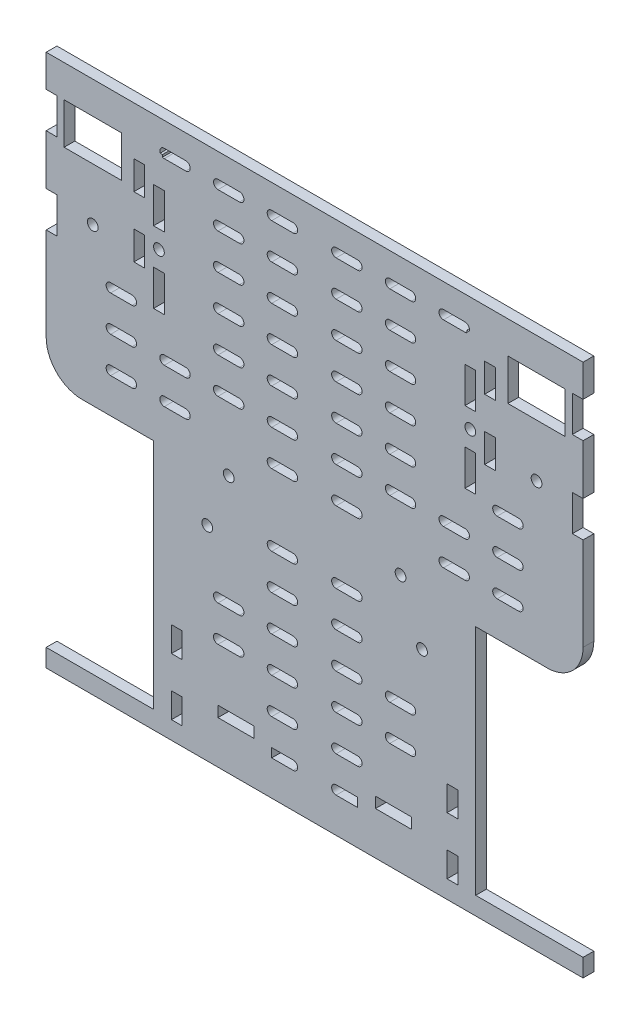
SolidWorks part; units mm, degrees
ref_plane "Alzado" through (0, 0, 0) normal (0, 0, 1) x (1, 0, 0)
ref_plane "Planta" through (0, 0, 0) normal (0, 1, 0) x (1, 0, 0)
ref_plane "Vista lateral" through (0, 0, 0) normal (1, 0, 0) x (0, 0, -1)
sketch "Croquis3" plane through (0, 0, 0) normal (0, 0, 1) x (1, 0, 0)
  line L1 (75, -75) -> (-75, -75)
  line L2 (75, -75) -> (75, 75)
  line L3 (75, 75) -> (-75, 75)
  line L4 (-75, -75) -> (-75, 75)
  line L5 (75, -75) -> (-75, 75) construction
  line L6 (75, 75) -> (-75, -75) construction
  line L11 (-75, -5) -> (-45, -5)
  line L13 (-75, -5) -> (-75, -70)
  line L18 (-75, -70) -> (-45, -70)
  line L19 (-45, -5) -> (-45, -70)
  line L24 (75, -70) -> (45, -70)
  line L25 (75, -70) -> (75, -5)
  line L26 (75, -5) -> (45, -5)
  line L27 (45, -70) -> (45, -5)
  point P0 (0, 0)
  dimension "D1" = 150
  dimension "D2" = 65
  dimension "D6" = 30
  dimension "D7" = 30
  dimension "D8" = 65
  dimension "D9" = 5
  dimension "D10" = 150
extrude "Saliente-Extruir1" add sketch "Croquis3" along normal blind 3
sketch "Croquis19" plane through (0, 0, 0) normal (0, 0, 1) x (1, 0, 0)
  line L0 (75, 75) -> (-75, 75) construction
  line L5 (-75, -5) -> (-75, 75) construction
  line B0 (-69, 31.75) -> (-55, 31.75) construction
  line B1 (-69, 62.75) -> (-69, 31.75) construction
  line B2 (-55, 62.75) -> (-69, 62.75) construction
  line B3 (-55, 31.75) -> (-55, 62.75) construction
  line B4 (-57, 56.5) -> (-57, 62) construction
  line B5 (-67, 56.5) -> (-57, 56.5) construction
  line B6 (-67, 62) -> (-67, 56.5) construction
  line B7 (-57, 62) -> (-67, 62) construction
  line B8 (-57, 34.35) -> (-67, 34.35) construction
  line B9 (-67, 34.35) -> (-67, 31.85) construction
  line B10 (-67, 31.85) -> (-57, 31.85) construction
  line B11 (-57, 31.85) -> (-57, 34.35) construction
  line B12 (-65.4, 33.45) -> (-66.1, 33.45) construction
  line B13 (-66.1, 33.45) -> (-66.1, 32.75) construction
  line B14 (-66.1, 32.75) -> (-65.4, 32.75) construction
  line B15 (-65.4, 32.75) -> (-65.4, 33.45) construction
  line B16 (-62.9, 33.45) -> (-63.6, 33.45) construction
  line B17 (-63.6, 33.45) -> (-63.6, 32.75) construction
  line B18 (-63.6, 32.75) -> (-62.9, 32.75) construction
  line B19 (-62.9, 32.75) -> (-62.9, 33.45) construction
  line B20 (-60.4, 33.45) -> (-61.1, 33.45) construction
  line B21 (-61.1, 33.45) -> (-61.1, 32.75) construction
  line B22 (-61.1, 32.75) -> (-60.4, 32.75) construction
  line B23 (-60.4, 32.75) -> (-60.4, 33.45) construction
  line B24 (-57.9, 33.45) -> (-58.6, 33.45) construction
  line B25 (-58.6, 33.45) -> (-58.6, 32.75) construction
  line B26 (-58.6, 32.75) -> (-57.9, 32.75) construction
  line B27 (-57.9, 32.75) -> (-57.9, 33.45) construction
  circle B28 centre (-62, 38.75) radius 1.5
  circle B29 centre (-60.25, 59.25) radius 1.5 construction
  circle B30 centre (-63.75, 59.25) radius 1.5 construction
  line B31 (-70, 53.5) -> (-54, 53.5)
  line B32 (-54, 53.5) -> (-54, 65)
  line B33 (-54, 65) -> (-70, 65)
  line B34 (-70, 65) -> (-70, 53.5)
  dimension "D1" = 10
  dimension "D2" = 5
sketch_block_instance "Bloque2-1"
sketch_block "Bloque2" parameters "D1"=3
extrude "Cortar-Extruir5" cut sketch "Croquis19" along normal blind 5
sketch "Croquis35" plane through (0, 0, 0) normal (0, 0, 1) x (1, 0, 0)
  line L0 (-45, -5) -> (-45, -70) construction
  line L1 (-40, -47) -> (-37, -47)
  line L2 (-40, -47) -> (-40, -54)
  line L3 (-40, -54) -> (-37, -54)
  line L4 (-37, -47) -> (-37, -54)
  line L5 (-40, -63) -> (-37, -63)
  line L6 (-40, -63) -> (-40, -70)
  line L7 (-40, -70) -> (-37, -70)
  line L8 (-37, -63) -> (-37, -70)
  line L9 (75, -75) -> (-75, -75) construction
  line L11 (-27, -63) -> (-17, -63)
  line L12 (-27, -63) -> (-27, -60)
  line L13 (-27, -60) -> (-17, -60)
  line L14 (-17, -63) -> (-17, -60)
  point P16 (-27, -61.5)
  dimension "D1" = 3
  dimension "D2" = 7
  dimension "D3" = 7
  dimension "D4" = 23
  dimension "D5" = 5
  dimension "D6" = 5
  dimension "D7" = 3
  dimension "D8" = 10
  dimension "D9" = 10
extrude "Cortar-Extruir7" cut sketch "Croquis35" along normal blind 3
sketch "Croquis36" plane through (0, 0, 0) normal (0, 0, 1) x (1, 0, 0)
  line L0 (-75, -5) -> (-75, 75) construction
  line L1 (-75, 65) -> (-72, 65)
  line L2 (-75, 65) -> (-75, 55)
  line L3 (-75, 55) -> (-72, 55)
  line L4 (-72, 65) -> (-72, 55)
  line L5 (75, 75) -> (-75, 75) construction
  line L6 (-75, 41) -> (-72, 41)
  line L7 (-75, 41) -> (-75, 31)
  line L8 (-75, 31) -> (-72, 31)
  line L9 (-72, 41) -> (-72, 31)
  dimension "D1" = 10
  dimension "D2" = 10
  dimension "D3" = 10
  dimension "D4" = 14
  dimension "D5" = 3
extrude "Cortar-Extruir8" cut sketch "Croquis36" along normal blind 3
sketch "Croquis37" plane through (0, 0, 0) normal (0, 0, 1) x (1, 0, 0)
  line L0 (-45, 47) -> (-42, 37) construction
  line L1 (45, 27) -> (-45, 27) construction
  line L2 (45, 27) -> (45, 57) construction
  line L3 (45, 57) -> (-45, 57) construction
  line L4 (-45, 27) -> (-45, 57) construction
  line L5 (45, 27) -> (-45, 57) construction
  line L6 (45, 57) -> (-45, 27) construction
  line L7 (-45, 57) -> (-42, 57)
  line L8 (-45, 57) -> (-45, 47)
  line L9 (-45, 47) -> (-42, 47)
  line L10 (-42, 57) -> (-42, 47)
  line L11 (-45, 27) -> (-42, 27)
  line L12 (-45, 27) -> (-45, 37)
  line L13 (-45, 37) -> (-42, 37)
  line L14 (-42, 27) -> (-42, 37)
  circle A0 centre (-43.5, 42) radius 1.5
  point P0 (0, 42)
  dimension "D4" = 3
  dimension "D1" = 90
  dimension "D2" = 30
  dimension "D3" = 3
  dimension "D5" = 10
  dimension "D6" = 10
  dimension "D7" = 42
extrude "Cortar-Extruir9" cut sketch "Croquis37" along normal blind 5
sketch "Croquis38" plane through (0, 0, 0) normal (0, 0, 1) x (1, 0, 0)
  line L0 (-70, 65) -> (-54, 65) construction
  line L1 (-50.5, 35.5) -> (-47.5, 35.5) construction
  line L2 (-50.5, 35.5) -> (-50.5, 60.5) construction
  line L3 (-50.5, 60.5) -> (-47.5, 60.5) construction
  line L4 (-47.5, 35.5) -> (-47.5, 60.5) construction
  line L5 (-50.5, 35.5) -> (-47.5, 60.5) construction
  line L6 (-50.5, 60.5) -> (-47.5, 35.5) construction
  line L7 (-50.5, 60.5) -> (-47.5, 60.5)
  line L8 (-50.5, 60.5) -> (-50.5, 52.5)
  line L9 (-50.5, 52.5) -> (-47.5, 52.5)
  line L10 (-47.5, 60.5) -> (-47.5, 52.5)
  line L11 (-47.5, 35.5) -> (-50.5, 35.5)
  line L12 (-47.5, 35.5) -> (-47.5, 43.5)
  line L13 (-47.5, 43.5) -> (-50.5, 43.5)
  line L14 (-50.5, 35.5) -> (-50.5, 43.5)
  line L15 (-45, 47) -> (-45, 57) construction
  point P0 (-49, 48)
  dimension "D1" = 3
  dimension "D2" = 25
  dimension "D3" = 8
  dimension "D4" = 8
  dimension "D5" = 4.5
  dimension "D6" = 2.5
extrude "Cortar-Extruir10" cut sketch "Croquis38" along normal blind 10
sketch "Croquis45" plane through (0, 0, 0) normal (0, 0, 1) x (1, 0, 0)
  line L1 (30, -18) -> (24, -18) construction
  line L2 (30, -18) -> (30, -3) construction
  line L3 (30, -3) -> (24, -3) construction
  line L4 (24, -18) -> (24, -3) construction
  line L5 (30, -18) -> (24, -3) construction
  line L6 (30, -3) -> (24, -18) construction
  line L7 (75, -75) -> (-75, -75) construction
  line L8 (75, -5) -> (75, 75) construction
  circle A0 centre (24, -3) radius 1.5
  circle A1 centre (30, -18) radius 1.5
  point P0 (27, -10.5)
  dimension "D1" = 3
  dimension "D2" = 51
  dimension "D3" = 72
  dimension "D4" = 3
  dimension "D5" = 15
  dimension "D6" = 6
extrude "Cortar-Extruir14" cut sketch "Croquis45" along normal through all
mirror "Simetría1" about plane through (0, 0, 0) normal (1, 0, 0) of "Cortar-Extruir14", "Cortar-Extruir9", "Cortar-Extruir8", "Cortar-Extruir7", "Cortar-Extruir5", "Cortar-Extruir10"
fillet "Redondeo1" radius 10 2 edges at (75, -5, 1.5) (-75, -5, 1.5)
sketch "Croquis40" plane through (0, 0, 0) normal (0, 0, 1) x (1, 0, 0)
  point P9 (54, 56)
  point P10 (24, 56)
  point P12 (39, 26)
  point P40 (24, 26)
  point P74 (24, 66)
  point P95 (9, 56)
  point P97 (39, 36)
  point P103 (54, 36)
  point P104 (9, 66)
  point P110 (54, 46)
  point P112 (39, 56)
  point P118 (24, 6)
  point P120 (39, 66)
  point P125 (39, 46)
  point P128 (9, 16)
  point P132 (24, 36)
  point P136 (9, 26)
  point P139 (69, 46)
  point P144 (9, 36)
  point P146 (69, 36)
  point P152 (9, 46)
  point P159 (24, 16)
  point P166 (69, 56)
  point P173 (69, 66)
  point P195 (24, 46)
  point P201 (54, 66)
  point P276 (39, 26)
  point P283 (39, 36)
  point P290 (54, 36)
  point P297 (54, 46)
  point P304 (24, 6)
  point P311 (39, 46)
  point P318 (24, 36)
  point P325 (69, 46)
  point P332 (69, 36)
  point P339 (69, 56)
  point P346 (69, 66)
  point P353 (24, 46)
  point P360 (54, 66)
  point P367 (54, 56)
  point P374 (39, 26)
  point P381 (39, 36)
  point P388 (54, 36)
  point P395 (54, 46)
  point P402 (24, 6)
  point P409 (39, 46)
  point P416 (24, 36)
  point P423 (69, 46)
  point P430 (69, 36)
  point P437 (69, 56)
  point P444 (69, 66)
  point P451 (24, 46)
  point P458 (54, 66)
  point P465 (54, 56)
  point P472 (39, 26)
  point P479 (39, 36)
  point P486 (54, 36)
  point P493 (54, 46)
  point P500 (24, 6)
  point P507 (39, 46)
  point P514 (24, 36)
  point P521 (69, 46)
  point P528 (69, 36)
  point P535 (69, 56)
  point P542 (69, 66)
  point P549 (24, 46)
  point P556 (54, 66)
  point P563 (54, 56)
  point P570 (39, 26)
  point P577 (39, 36)
  point P584 (54, 36)
  point P591 (54, 46)
  point P598 (24, 6)
  point P605 (39, 46)
  point P612 (24, 36)
  point P619 (69, 46)
  point P626 (69, 36)
  point P633 (69, 56)
  point P640 (69, 66)
  point P647 (24, 46)
  point P654 (54, 66)
  point P661 (54, 56)
  line B0 (-70, 48.5) -> (-55.5, 48.5)
  line B1 (-32, -68) -> (-32, -70)
  line B2 (-49, 65.5) -> (-49, 70)
  line B3 (-67, 34.5967) -> (-67, 26)
  line B4 (37, 35.5) -> (37, 22)
  line B5 (-37, 48.5) -> (-37, 62)
  line B6 (-50, 30.5) -> (-50, 22)
  line B7 (42.5, 62) -> (37, 62)
  line B8 (67, 42.9033) -> (67, 46)
  line B9 (32, -68) -> (32, -70)
  line B10 (-28, -9) -> (-15, -9)
  line B11 (-15, 4) -> (-15, 11)
  line B12 (-15, 11) -> (-28, 11)
  line B13 (-28, 11) -> (-28, -9)
  line B14 (-28, -35) -> (-15, -35)
  line B15 (-15, -35) -> (-15, -15)
  line B16 (-15, -15) -> (-28, -15)
  line B17 (-28, -15) -> (-28, -35)
  line B18 (-17, -9) -> (1, -9)
  line B19 (1, 4) -> (-15, 4)
  line B20 (-32, -68) -> (-12, -68)
  line B21 (-12, -68) -> (-12, -55)
  line B22 (-12, -55) -> (-32, -55)
  line B23 (-32, -42) -> (-32, -55)
  line B24 (-32, -42) -> (-40, -42)
  line B25 (-37, 35.5) -> (-12, 35.5)
  line B26 (-12, 35.5) -> (-12, 48.5)
  line B27 (-12, 48.5) -> (-37, 48.5)
  line B28 (-50, 22) -> (-37, 22)
  line B29 (-37, 22) -> (-37, 35.5)
  line B30 (-37, 62) -> (-42.5, 62)
  line B31 (-55.5, 30.5) -> (-50, 30.5)
  line B32 (-55.5, 48.5) -> (-55.5, 30.5)
  line B33 (-42.5, 65.5) -> (-49, 65.5)
  line B34 (-42.5, 62) -> (-42.5, 65.5)
  line B35 (49, 70) -> (49, 65.5)
  line B36 (55.5, 48.5) -> (70, 48.5)
  line B37 (28, -9) -> (28, 11)
  line B38 (28, 11) -> (15, 11)
  line B39 (15, 11) -> (15, 4)
  line B40 (15, -9) -> (28, -9)
  line B41 (28, -35) -> (28, -15)
  line B42 (28, -15) -> (15, -15)
  line B43 (15, -15) -> (15, -35)
  line B44 (15, -35) -> (28, -35)
  line B45 (15, 4) -> (-1, 4)
  line B46 (-1, -9) -> (17, -9)
  line B47 (32, -55) -> (12, -55)
  line B48 (12, -55) -> (12, -68)
  line B49 (12, -68) -> (32, -68)
  line B50 (32, -42) -> (32, -55)
  line B51 (40, -42) -> (32, -42)
  line B52 (37, 48.5) -> (12, 48.5)
  line B53 (12, 48.5) -> (12, 35.5)
  line B54 (12, 35.5) -> (37, 35.5)
  line B55 (50, 22) -> (50, 30.5)
  line B56 (37, 62) -> (37, 48.5)
  line B57 (37, 22) -> (50, 22)
  line B58 (55.5, 30.5) -> (55.5, 48.5)
  line B59 (50, 30.5) -> (55.5, 30.5)
  line B60 (42.5, 65.5) -> (42.5, 62)
  line B61 (49, 65.5) -> (42.5, 65.5)
  line B62 (49, 70) -> (-49, 70)
  line B63 (-70, 48.5) -> (-70, 46)
  line B64 (-70, 46) -> (-67, 46)
  line B65 (-67, 46) -> (-67, 42.9033)
  line B66 (-67, 26) -> (-70, 26)
  line B67 (-70, 26) -> (-70, 5)
  line B68 (-65, 0) -> (-40, 0)
  line B69 (-40, 0) -> (-40, -42)
  line B70 (-32, -70) -> (32, -70)
  line B71 (40, -42) -> (40, 0)
  line B72 (40, 0) -> (65, 0)
  line B73 (70, 5) -> (70, 26)
  line B74 (70, 26) -> (67, 26)
  line B75 (67, 26) -> (67, 34.5967)
  line B76 (67, 46) -> (70, 46)
  line B77 (70, 46) -> (70, 48.5)
  arc B78 (-67, 34.5967) -> (-67, 42.9033) centre (-62, 38.75) ccw
  arc B79 (67, 42.9033) -> (67, 34.5967) centre (62, 38.75) ccw
  arc B80 (-70, 5) -> (-65, 0) centre (-65, 5) ccw
  arc B81 (65, 0) -> (70, 5) centre (65, 5) ccw
sketch_block_instance "Bloque3-1"
sketch_block "Bloque3"
sketch "Croquis42" plane through (0, 0, 0) normal (0, 0, 1) x (1, 0, 0)
  line L4 (6, 6) -> (12, 6) construction
  line L5 (6, 7.25) -> (12, 7.25)
  line L6 (6, 4.75) -> (12, 4.75)
  line L14 (36, 6) -> (42, 6) construction
  line L15 (36, 7.25) -> (42, 7.25)
  line L20 (36, 4.75) -> (42, 4.75)
  line L21 (51, 6) -> (57, 6) construction
  line L22 (51, 7.25) -> (57, 7.25)
  line L23 (51, 4.75) -> (57, 4.75)
  line L31 (21, 16) -> (27, 16) construction
  line L36 (21, 17.25) -> (27, 17.25)
  line L37 (21, 14.75) -> (27, 14.75)
  line L38 (36, 16) -> (42, 16) construction
  line L39 (36, 17.25) -> (42, 17.25)
  line L44 (36, 14.75) -> (42, 14.75)
  line L45 (51, 16) -> (57, 16) construction
  line L47 (51, 17.25) -> (57, 17.25)
  line L53 (51, 14.75) -> (57, 14.75)
  line L63 (21, 26) -> (27, 26) construction
  line L70 (21, 27.25) -> (27, 27.25)
  line L71 (21, 24.75) -> (27, 24.75)
  line L85 (51, 26) -> (57, 26) construction
  line L86 (51, 27.25) -> (57, 27.25)
  line L87 (51, 24.75) -> (57, 24.75)
  line L109 (42.5, 65.5) -> (42.5, 62) construction
  line L116 (49, 65.5) -> (42.5, 65.5) construction
  line L148 (21, 56) -> (27, 56) construction
  line L149 (21, 57.25) -> (27, 57.25)
  line L150 (21, 54.75) -> (27, 54.75)
  line L158 (42.5, 65.5) -> (42.5, 64.8544)
  line L165 (43.1456, 65.5) -> (42.5, 65.5)
  line L172 (21, 66) -> (27, 66) construction
  line L173 (21, 67.25) -> (27, 67.25)
  line L174 (21, 64.75) -> (27, 64.75)
  line L175 (36, 66) -> (42, 66) construction
  line L180 (36, 67.25) -> (42, 67.25)
  line L181 (36, 64.75) -> (42, 64.75)
  line L220 (6, 16) -> (12, 16) construction
  line L221 (6, 17.25) -> (12, 17.25)
  line L222 (6, 14.75) -> (12, 14.75)
  line L223 (6, 26) -> (12, 26) construction
  line L224 (6, 27.25) -> (12, 27.25)
  line L225 (6, 24.75) -> (12, 24.75)
  line L232 (6, 56) -> (12, 56) construction
  line L233 (6, 57.25) -> (12, 57.25)
  line L234 (6, 54.75) -> (12, 54.75)
  line L235 (6, 66) -> (12, 66) construction
  line L236 (6, 67.25) -> (12, 67.25)
  line L237 (6, 64.75) -> (12, 64.75)
  line L1105 (36, 66) -> (42, 66) construction
  line L1106 (36, 67.25) -> (42, 67.25)
  line L1107 (36, 64.75) -> (42, 64.75)
  line L1108 (36, 56) -> (42, 56) construction
  line L1109 (36, 57.25) -> (42, 57.25)
  line L1110 (36, 54.75) -> (42, 54.75)
  line L1111 (6, 46) -> (12, 46) construction
  line L1112 (6, 47.25) -> (12, 47.25)
  line L1113 (6, 44.75) -> (12, 44.75)
  line L1114 (6, 36) -> (12, 36) construction
  line L1115 (6, 37.25) -> (12, 37.25)
  line L1116 (6, 34.75) -> (12, 34.75)
  line L1117 (66, 16) -> (72, 16) construction
  line L1118 (66, 17.25) -> (72, 17.25)
  line L1119 (66, 14.75) -> (72, 14.75)
  line L1120 (66, 6) -> (72, 6) construction
  line L1121 (66, 7.25) -> (72, 7.25)
  line L1122 (66, 4.75) -> (72, 4.75)
  line L1123 (66, 26) -> (72, 26) construction
  line L1124 (66, 27.25) -> (72, 27.25)
  line L1125 (66, 24.75) -> (72, 24.75)
  line L1126 (36, 26) -> (42, 26) construction
  line L1127 (36, 27.25) -> (42, 27.25)
  line L1128 (36, 24.75) -> (42, 24.75)
  line L1129 (36, 36) -> (42, 36) construction
  line L1130 (36, 37.25) -> (42, 37.25)
  line L1131 (36, 34.75) -> (42, 34.75)
  line L1132 (51, 36) -> (57, 36) construction
  line L1133 (51, 37.25) -> (57, 37.25)
  line L1134 (51, 34.75) -> (57, 34.75)
  line L1135 (51, 46) -> (57, 46) construction
  line L1136 (51, 47.25) -> (57, 47.25)
  line L1137 (51, 44.75) -> (57, 44.75)
  line L1138 (21, 6) -> (27, 6) construction
  line L1139 (21, 7.25) -> (27, 7.25)
  line L1140 (21, 4.75) -> (27, 4.75)
  line L1141 (36, 46) -> (42, 46) construction
  line L1142 (36, 47.25) -> (42, 47.25)
  line L1143 (36, 44.75) -> (42, 44.75)
  line L1144 (21, 36) -> (27, 36) construction
  line L1145 (21, 37.25) -> (27, 37.25)
  line L1146 (21, 34.75) -> (27, 34.75)
  line L1147 (66, 46) -> (72, 46) construction
  line L1148 (66, 47.25) -> (72, 47.25)
  line L1149 (66, 44.75) -> (72, 44.75)
  line L1150 (66, 36) -> (72, 36) construction
  line L1151 (66, 37.25) -> (72, 37.25)
  line L1152 (66, 34.75) -> (72, 34.75)
  line L1153 (66, 56) -> (72, 56) construction
  line L1154 (66, 57.25) -> (72, 57.25)
  line L1155 (66, 54.75) -> (72, 54.75)
  line L1156 (66, 66) -> (72, 66) construction
  line L1157 (66, 67.25) -> (72, 67.25)
  line L1158 (66, 64.75) -> (72, 64.75)
  line L1159 (21, 46) -> (27, 46) construction
  line L1160 (21, 47.25) -> (27, 47.25)
  line L1161 (21, 44.75) -> (27, 44.75)
  line L1162 (51, 66) -> (57, 66) construction
  line L1163 (51, 67.25) -> (57, 67.25)
  line L1164 (51, 64.75) -> (57, 64.75)
  line L1165 (51, 56) -> (57, 56) construction
  line L1166 (51, 57.25) -> (57, 57.25)
  line L1167 (51, 54.75) -> (57, 54.75)
  line L1168 (36, 66) -> (42, 66) construction
  line L1169 (36, 67.25) -> (42, 67.25)
  line L1170 (36, 64.75) -> (42, 64.75)
  line L1171 (36, 56) -> (42, 56) construction
  line L1172 (36, 57.25) -> (42, 57.25)
  line L1173 (36, 54.75) -> (42, 54.75)
  line L1174 (6, 46) -> (12, 46) construction
  line L1175 (6, 47.25) -> (12, 47.25)
  line L1176 (6, 44.75) -> (12, 44.75)
  line L1177 (6, 36) -> (12, 36) construction
  line L1178 (6, 37.25) -> (12, 37.25)
  line L1179 (6, 34.75) -> (12, 34.75)
  line L1180 (66, 16) -> (72, 16) construction
  line L1181 (66, 17.25) -> (72, 17.25)
  line L1182 (66, 14.75) -> (72, 14.75)
  line L1183 (66, 6) -> (72, 6) construction
  line L1184 (66, 7.25) -> (72, 7.25)
  line L1185 (66, 4.75) -> (72, 4.75)
  line L1186 (66, 26) -> (72, 26) construction
  line L1187 (66, 27.25) -> (72, 27.25)
  line L1188 (66, 24.75) -> (72, 24.75)
  line L1189 (36, 26) -> (42, 26) construction
  line L1190 (36, 27.25) -> (42, 27.25)
  line L1191 (36, 24.75) -> (42, 24.75)
  line L1192 (36, 36) -> (42, 36) construction
  line L1193 (36, 37.25) -> (42, 37.25)
  line L1194 (36, 34.75) -> (42, 34.75)
  line L1195 (51, 36) -> (57, 36) construction
  line L1196 (51, 37.25) -> (57, 37.25)
  line L1197 (51, 34.75) -> (57, 34.75)
  line L1198 (51, 46) -> (57, 46) construction
  line L1199 (51, 47.25) -> (57, 47.25)
  line L1200 (51, 44.75) -> (57, 44.75)
  line L1201 (21, 6) -> (27, 6) construction
  line L1202 (21, 7.25) -> (27, 7.25)
  line L1203 (21, 4.75) -> (27, 4.75)
  line L1204 (36, 46) -> (42, 46) construction
  line L1205 (36, 47.25) -> (42, 47.25)
  line L1206 (36, 44.75) -> (42, 44.75)
  line L1207 (21, 36) -> (27, 36) construction
  line L1208 (21, 37.25) -> (27, 37.25)
  line L1209 (21, 34.75) -> (27, 34.75)
  line L1210 (66, 46) -> (72, 46) construction
  line L1211 (66, 47.25) -> (72, 47.25)
  line L1212 (66, 44.75) -> (72, 44.75)
  line L1213 (66, 36) -> (72, 36) construction
  line L1214 (66, 37.25) -> (72, 37.25)
  line L1215 (66, 34.75) -> (72, 34.75)
  line L1216 (66, 56) -> (72, 56) construction
  line L1217 (66, 57.25) -> (72, 57.25)
  line L1218 (66, 54.75) -> (72, 54.75)
  line L1219 (66, 66) -> (72, 66) construction
  line L1220 (66, 67.25) -> (72, 67.25)
  line L1221 (66, 64.75) -> (72, 64.75)
  line L1222 (21, 46) -> (27, 46) construction
  line L1223 (21, 47.25) -> (27, 47.25)
  line L1224 (21, 44.75) -> (27, 44.75)
  line L1225 (51, 66) -> (57, 66) construction
  line L1226 (51, 67.25) -> (57, 67.25)
  line L1227 (51, 64.75) -> (57, 64.75)
  line L1228 (51, 56) -> (57, 56) construction
  line L1229 (51, 57.25) -> (57, 57.25)
  line L1230 (51, 54.75) -> (57, 54.75)
  arc A1 (6, 7.25) -> (6, 4.75) centre (6, 6) ccw
  arc A3 (12, 4.75) -> (12, 7.25) centre (12, 6) ccw
  arc A12 (36, 7.25) -> (36, 4.75) centre (36, 6) ccw
  arc A13 (42, 4.75) -> (42, 7.25) centre (42, 6) ccw
  arc A14 (51, 7.25) -> (51, 4.75) centre (51, 6) ccw
  arc A15 (57, 4.75) -> (57, 7.25) centre (57, 6) ccw
  arc A18 (21, 17.25) -> (21, 14.75) centre (21, 16) ccw
  arc A19 (27, 14.75) -> (27, 17.25) centre (27, 16) ccw
  arc A20 (36, 17.25) -> (36, 14.75) centre (36, 16) ccw
  arc A21 (42, 14.75) -> (42, 17.25) centre (42, 16) ccw
  arc A22 (51, 17.25) -> (51, 14.75) centre (51, 16) ccw
  arc A23 (57, 14.75) -> (57, 17.25) centre (57, 16) ccw
  arc A26 (21, 27.25) -> (21, 24.75) centre (21, 26) ccw
  arc A27 (27, 24.75) -> (27, 27.25) centre (27, 26) ccw
  arc A30 (51, 27.25) -> (51, 24.75) centre (51, 26) ccw
  arc A31 (57, 24.75) -> (57, 27.25) centre (57, 26) ccw
  arc A50 (21, 57.25) -> (21, 54.75) centre (21, 56) ccw
  arc A51 (27, 54.75) -> (27, 57.25) centre (27, 56) ccw
  arc A58 (21, 67.25) -> (21, 64.75) centre (21, 66) ccw
  arc A59 (27, 64.75) -> (27, 67.25) centre (27, 66) ccw
  arc A60 (36, 67.25) -> (36, 64.75) centre (36, 66) ccw
  arc A61 (42, 64.75) -> (42.5, 64.8544) centre (42, 66) ccw
  arc A66 (6, 17.25) -> (6, 14.75) centre (6, 16) ccw
  arc A67 (12, 14.75) -> (12, 17.25) centre (12, 16) ccw
  arc A68 (6, 27.25) -> (6, 24.75) centre (6, 26) ccw
  arc A69 (12, 24.75) -> (12, 27.25) centre (12, 26) ccw
  arc A74 (6, 57.25) -> (6, 54.75) centre (6, 56) ccw
  arc A75 (12, 54.75) -> (12, 57.25) centre (12, 56) ccw
  arc A76 (6, 67.25) -> (6, 64.75) centre (6, 66) ccw
  arc A77 (12, 64.75) -> (12, 67.25) centre (12, 66) ccw
  arc A82 (43.1456, 65.5) -> (42, 67.25) centre (42, 66) ccw
  arc A624 (36, 67.25) -> (36, 64.75) centre (36, 66) ccw
  arc A625 (42, 64.75) -> (42, 67.25) centre (42, 66) ccw
  arc A626 (36, 57.25) -> (36, 54.75) centre (36, 56) ccw
  arc A627 (42, 54.75) -> (42, 57.25) centre (42, 56) ccw
  arc A628 (6, 47.25) -> (6, 44.75) centre (6, 46) ccw
  arc A629 (12, 44.75) -> (12, 47.25) centre (12, 46) ccw
  arc A630 (6, 37.25) -> (6, 34.75) centre (6, 36) ccw
  arc A631 (12, 34.75) -> (12, 37.25) centre (12, 36) ccw
  arc A632 (66, 17.25) -> (66, 14.75) centre (66, 16) ccw
  arc A633 (72, 14.75) -> (72, 17.25) centre (72, 16) ccw
  arc A634 (66, 7.25) -> (66, 4.75) centre (66, 6) ccw
  arc A635 (72, 4.75) -> (72, 7.25) centre (72, 6) ccw
  arc A636 (66, 27.25) -> (66, 24.75) centre (66, 26) ccw
  arc A637 (72, 24.75) -> (72, 27.25) centre (72, 26) ccw
  arc A638 (36, 27.25) -> (36, 24.75) centre (36, 26) ccw
  arc A639 (42, 24.75) -> (42, 27.25) centre (42, 26) ccw
  arc A640 (36, 37.25) -> (36, 34.75) centre (36, 36) ccw
  arc A641 (42, 34.75) -> (42, 37.25) centre (42, 36) ccw
  arc A642 (51, 37.25) -> (51, 34.75) centre (51, 36) ccw
  arc A643 (57, 34.75) -> (57, 37.25) centre (57, 36) ccw
  arc A644 (51, 47.25) -> (51, 44.75) centre (51, 46) ccw
  arc A645 (57, 44.75) -> (57, 47.25) centre (57, 46) ccw
  arc A646 (21, 7.25) -> (21, 4.75) centre (21, 6) ccw
  arc A647 (27, 4.75) -> (27, 7.25) centre (27, 6) ccw
  arc A648 (36, 47.25) -> (36, 44.75) centre (36, 46) ccw
  arc A649 (42, 44.75) -> (42, 47.25) centre (42, 46) ccw
  arc A650 (21, 37.25) -> (21, 34.75) centre (21, 36) ccw
  arc A651 (27, 34.75) -> (27, 37.25) centre (27, 36) ccw
  arc A652 (66, 47.25) -> (66, 44.75) centre (66, 46) ccw
  arc A653 (72, 44.75) -> (72, 47.25) centre (72, 46) ccw
  arc A654 (66, 37.25) -> (66, 34.75) centre (66, 36) ccw
  arc A655 (72, 34.75) -> (72, 37.25) centre (72, 36) ccw
  arc A656 (66, 57.25) -> (66, 54.75) centre (66, 56) ccw
  arc A657 (72, 54.75) -> (72, 57.25) centre (72, 56) ccw
  arc A658 (66, 67.25) -> (66, 64.75) centre (66, 66) ccw
  arc A659 (72, 64.75) -> (72, 67.25) centre (72, 66) ccw
  arc A660 (21, 47.25) -> (21, 44.75) centre (21, 46) ccw
  arc A661 (27, 44.75) -> (27, 47.25) centre (27, 46) ccw
  arc A662 (51, 67.25) -> (51, 64.75) centre (51, 66) ccw
  arc A663 (57, 64.75) -> (57, 67.25) centre (57, 66) ccw
  arc A664 (51, 57.25) -> (51, 54.75) centre (51, 56) ccw
  arc A665 (57, 54.75) -> (57, 57.25) centre (57, 56) ccw
  point P2 (9, 6)
  point P8 (6, 46)
  point P9 (54, 56)
  point P10 (6, 36)
  point P12 (39, 26)
  point P19 (39, 6)
  point P26 (54, 6)
  point P40 (24, 16)
  point P47 (39, 16)
  point P54 (54, 16)
  point P68 (24, 26)
  point P82 (54, 26)
  point P94 (39, 66)
  point P97 (39, 36)
  point P103 (54, 36)
  point P104 (39, 56)
  point P110 (54, 46)
  point P114 (9, 46)
  point P118 (24, 6)
  point P123 (9, 36)
  point P125 (39, 46)
  point P132 (24, 36)
  point P133 (69, 16)
  point P139 (69, 46)
  point P143 (69, 6)
  point P146 (69, 36)
  point P152 (24, 56)
  point P166 (69, 56)
  point P169 (69, 26)
  point P173 (69, 66)
  point P180 (24, 66)
  point P187 (39, 66)
  point P195 (24, 46)
  point P201 (54, 66)
  point P208 (9, 16)
  point P215 (9, 26)
  point P236 (9, 56)
  point P243 (9, 66)
  point P276 (39, 26)
  point P283 (39, 36)
  point P290 (54, 36)
  point P297 (54, 46)
  point P304 (24, 6)
  point P311 (39, 46)
  point P318 (24, 36)
  point P325 (69, 46)
  point P332 (69, 36)
  point P339 (69, 56)
  point P346 (69, 66)
  point P353 (24, 46)
  point P360 (54, 66)
  point P367 (54, 56)
  point P374 (39, 26)
  point P381 (39, 36)
  point P388 (54, 36)
  point P395 (54, 46)
  point P402 (24, 6)
  point P409 (39, 46)
  point P416 (24, 36)
  point P423 (69, 46)
  point P430 (69, 36)
  point P437 (69, 56)
  point P444 (69, 66)
  point P451 (24, 46)
  point P458 (54, 66)
  point P465 (54, 56)
  point P472 (39, 26)
  point P479 (39, 36)
  point P486 (54, 36)
  point P493 (54, 46)
  point P500 (24, 6)
  point P507 (39, 46)
  point P514 (24, 36)
  point P521 (69, 46)
  point P528 (69, 36)
  point P535 (69, 56)
  point P542 (69, 66)
  point P549 (24, 46)
  point P556 (54, 66)
  point P563 (54, 56)
  point P570 (39, 26)
  point P577 (39, 36)
  point P584 (54, 36)
  point P591 (54, 46)
  point P598 (24, 6)
  point P605 (39, 46)
  point P612 (24, 36)
  point P619 (69, 46)
  point P626 (69, 36)
  point P633 (69, 56)
  point P640 (69, 66)
  point P647 (24, 46)
  point P654 (54, 66)
  point P661 (54, 56)
  point P668 (39, 26)
  point P675 (39, 36)
  point P682 (54, 36)
  point P689 (54, 46)
  point P696 (24, 6)
  point P703 (39, 46)
  point P710 (24, 36)
  point P717 (69, 46)
  point P724 (69, 36)
  point P731 (69, 56)
  point P738 (69, 66)
  point P745 (24, 46)
  point P752 (54, 66)
  point P759 (54, 56)
  point P766 (39, 26)
  point P773 (39, 36)
  point P780 (54, 36)
  point P787 (54, 46)
  point P794 (24, 6)
  point P801 (39, 46)
  point P808 (24, 36)
  point P815 (69, 46)
  point P822 (69, 36)
  point P829 (69, 56)
  point P836 (69, 66)
  point P843 (24, 46)
  point P850 (54, 66)
  point P857 (54, 56)
  point P864 (39, 26)
  point P871 (39, 36)
  point P878 (54, 36)
  point P885 (54, 46)
  point P892 (24, 6)
  point P899 (39, 46)
  point P906 (24, 36)
  point P913 (69, 46)
  point P920 (69, 36)
  point P927 (69, 56)
  point P934 (69, 66)
  point P941 (24, 46)
  point P948 (54, 66)
  point P955 (54, 56)
  point P962 (39, 26)
  point P969 (39, 36)
  point P976 (54, 36)
  point P983 (54, 46)
  point P990 (24, 6)
  point P997 (39, 46)
  point P1004 (24, 36)
  point P1011 (69, 46)
  point P1018 (69, 36)
  point P1025 (69, 56)
  point P1032 (69, 66)
  point P1039 (24, 46)
  point P1046 (54, 66)
  point P1053 (54, 56)
  point P1060 (39, 66)
  point P1067 (39, 56)
  point P1074 (9, 46)
  point P1081 (9, 36)
  point P1088 (69, 16)
  point P1095 (69, 6)
  point P1102 (69, 26)
  point P1109 (39, 26)
  point P1116 (39, 36)
  point P1123 (54, 36)
  point P1130 (54, 46)
  point P1137 (24, 6)
  point P1144 (39, 46)
  point P1151 (24, 36)
  point P1158 (69, 46)
  point P1165 (69, 36)
  point P1172 (69, 56)
  point P1179 (69, 66)
  point P1186 (24, 46)
  point P1193 (54, 66)
  point P1200 (54, 56)
  point P1207 (39, 66)
  point P1214 (39, 56)
  point P1221 (9, 46)
  point P1228 (9, 36)
  point P1235 (69, 16)
  point P1242 (69, 6)
  point P1249 (69, 26)
  point P1256 (39, 26)
  point P1263 (39, 36)
  point P1270 (54, 36)
  point P1277 (54, 46)
  point P1284 (24, 6)
  point P1291 (39, 46)
  point P1298 (24, 36)
  point P1305 (69, 46)
  point P1312 (69, 36)
  point P1319 (69, 56)
  point P1326 (69, 66)
  point P1333 (24, 46)
  point P1340 (54, 66)
  point P1347 (54, 56)
  point P1354 (39, 66)
  point P1361 (39, 56)
  point P1368 (9, 46)
  point P1375 (9, 36)
  point P1382 (69, 16)
  point P1389 (69, 6)
  point P1396 (69, 26)
  point P1403 (39, 26)
  point P1410 (39, 36)
  point P1417 (54, 36)
  point P1424 (54, 46)
  point P1431 (24, 6)
  point P1438 (39, 46)
  point P1445 (24, 36)
  point P1452 (69, 46)
  point P1459 (69, 36)
  point P1466 (69, 56)
  point P1473 (69, 66)
  point P1480 (24, 46)
  point P1487 (54, 66)
  point P1494 (54, 56)
  point P1501 (39, 66)
  point P1508 (39, 56)
  point P1515 (9, 46)
  point P1522 (9, 36)
  point P1529 (69, 16)
  point P1536 (69, 6)
  point P1543 (69, 26)
  point P1550 (39, 26)
  point P1557 (39, 36)
  point P1564 (54, 36)
  point P1571 (54, 46)
  point P1578 (24, 6)
  point P1585 (39, 46)
  point P1592 (24, 36)
  point P1599 (69, 46)
  point P1606 (69, 36)
  point P1613 (69, 56)
  point P1620 (69, 66)
  point P1627 (24, 46)
  point P1634 (54, 66)
  point P1641 (54, 56)
  point P1648 (39, 66)
  point P1655 (39, 56)
  point P1662 (9, 46)
  point P1669 (9, 36)
  point P1676 (69, 16)
  point P1683 (69, 6)
  point P1690 (69, 26)
  point P1697 (39, 26)
  point P1704 (39, 36)
  point P1711 (54, 36)
  point P1718 (54, 46)
  point P1725 (24, 6)
  point P1732 (39, 46)
  point P1739 (24, 36)
  point P1746 (69, 46)
  point P1753 (69, 36)
  point P1760 (69, 56)
  point P1767 (69, 66)
  point P1774 (24, 46)
  point P1781 (54, 66)
  point P1788 (54, 56)
  point P1795 (39, 66)
  point P1802 (39, 56)
  point P1809 (9, 46)
  point P1816 (9, 36)
  point P1823 (69, 16)
  point P1830 (69, 6)
  point P1837 (69, 26)
  point P1844 (39, 26)
  point P1851 (39, 36)
  point P1858 (54, 36)
  point P1865 (54, 46)
  point P1872 (24, 6)
  point P1879 (39, 46)
  point P1886 (24, 36)
  point P1893 (69, 46)
  point P1900 (69, 36)
  point P1907 (69, 56)
  point P1914 (69, 66)
  point P1921 (24, 46)
  point P1928 (54, 66)
  point P1935 (54, 56)
  point P1942 (39, 66)
  point P1949 (39, 56)
  point P1956 (9, 46)
  point P1963 (9, 36)
  point P1970 (69, 16)
  point P1977 (69, 6)
  point P1984 (69, 26)
  point P1991 (39, 26)
  point P1998 (39, 36)
  point P2005 (54, 36)
  point P2012 (54, 46)
  point P2019 (24, 6)
  point P2026 (39, 46)
  point P2033 (24, 36)
  point P2040 (69, 46)
  point P2047 (69, 36)
  point P2054 (69, 56)
  point P2061 (69, 66)
  point P2068 (24, 46)
  point P2075 (54, 66)
  point P2082 (54, 56)
  point P2089 (39, 66)
  point P2096 (39, 56)
  point P2103 (9, 46)
  point P2110 (9, 36)
  point P2117 (69, 16)
  point P2124 (69, 6)
  point P2131 (69, 26)
  point P2138 (39, 26)
  point P2145 (39, 36)
  point P2152 (54, 36)
  point P2159 (54, 46)
  point P2166 (24, 6)
  point P2173 (39, 46)
  point P2180 (24, 36)
  point P2187 (69, 46)
  point P2194 (69, 36)
  point P2201 (69, 56)
  point P2208 (69, 66)
  point P2215 (24, 46)
  point P2222 (54, 66)
  point P2229 (54, 56)
  line B0 (6, 47.25) -> (12, 47.25)
  arc B1 (12, 44.75) -> (12, 47.25) centre (12, 46) ccw
  line B2 (6, 44.75) -> (12, 44.75)
  arc B3 (6, 47.25) -> (6, 44.75) centre (6, 46) ccw
  line B4 (6, 37.25) -> (12, 37.25)
  arc B5 (12, 34.75) -> (12, 37.25) centre (12, 36) ccw
  line B6 (6, 34.75) -> (12, 34.75)
  arc B7 (6, 37.25) -> (6, 34.75) centre (6, 36) ccw
  line B8 (21, 47.25) -> (27, 47.25)
  arc B9 (27, 44.75) -> (27, 47.25) centre (27, 46) ccw
  line B10 (21, 44.75) -> (27, 44.75)
  arc B11 (21, 47.25) -> (21, 44.75) centre (21, 46) ccw
  line B12 (21, 37.25) -> (27, 37.25)
  arc B13 (27, 34.75) -> (27, 37.25) centre (27, 36) ccw
  line B14 (21, 34.75) -> (27, 34.75)
  arc B15 (21, 37.25) -> (21, 34.75) centre (21, 36) ccw
  dimension "D1" = 6
  dimension "D2" = 2.5
  dimension "D5" = 5
  dimension "D6" = 7
sketch_block_instance "Bloque4-1"
sketch_block "Bloque4"
sketch_block_instance "Bloque4-2"
sketch_block_instance "Bloque4-3"
sketch_block_instance "Bloque4-4"
extrude "Cortar-Extruir11" cut sketch "Croquis42" along normal blind 10
mirror "Simetría2" about plane through (0, 0, 0) normal (1, 0, 0) of "Cortar-Extruir11"
sketch "Croquis43" plane through (0, 0, 0) normal (0, 0, 1) x (1, 0, 0)
  line L2 (6, 4.75) -> (12, 4.75)
  line L3 (12, 7.25) -> (6, 7.25)
  line L4 (6, 4.75) -> (12, 4.75)
  line L5 (12, 7.25) -> (6, 7.25)
  line L6 (-12, 4.75) -> (-6, 4.75)
  line L7 (-6, 7.25) -> (-12, 7.25)
  line L8 (-12, 4.75) -> (-6, 4.75)
  line L9 (-6, 7.25) -> (-12, 7.25)
  line L12 (-6, -12.75) -> (-12, -12.75)
  line L13 (-12, -15.25) -> (-6, -15.25)
  line L14 (12, -12.75) -> (6, -12.75)
  line L15 (6, -15.25) -> (12, -15.25)
  line L16 (-6, -22.75) -> (-12, -22.75)
  line L17 (-12, -25.25) -> (-6, -25.25)
  line L18 (12, -22.75) -> (6, -22.75)
  line L19 (6, -25.25) -> (12, -25.25)
  line L20 (-6, -32.75) -> (-12, -32.75)
  line L21 (-12, -35.25) -> (-6, -35.25)
  line L22 (12, -32.75) -> (6, -32.75)
  line L23 (6, -35.25) -> (12, -35.25)
  line L24 (-6, -42.75) -> (-12, -42.75)
  line L25 (-12, -45.25) -> (-6, -45.25)
  line L26 (12, -42.75) -> (6, -42.75)
  line L27 (6, -45.25) -> (12, -45.25)
  line L28 (-6, -52.75) -> (-12, -52.75)
  line L29 (-12, -55.25) -> (-6, -55.25)
  line L30 (12, -52.75) -> (6, -52.75)
  line L31 (6, -55.25) -> (12, -55.25)
  line L32 (-6, -62.75) -> (-12, -62.75)
  line L33 (-12, -65.25) -> (-6, -65.25)
  line L34 (12, -62.75) -> (6, -62.75)
  line L35 (6, -65.25) -> (12, -65.25)
  line L36 (-21, -42.75) -> (-27, -42.75)
  line L37 (-12, -68) -> (-12, -55) construction
  line L38 (27, -42.75) -> (21, -42.75)
  line L39 (-12, -65.25) -> (-12, -62.75)
  line L40 (21, -45.25) -> (27, -45.25)
  line L41 (12, -62.75) -> (12, -65.25)
  line L42 (-6, -2.75) -> (-12, -2.75) [skipped]
  line L43 (-12, -5.25) -> (-6, -5.25) [skipped]
  line L44 (12, -2.75) -> (6, -2.75) [skipped]
  line L45 (6, -5.25) -> (12, -5.25) [skipped]
  line L46 (-27, -45.25) -> (-21, -45.25)
  line L47 (-21, -32.75) -> (-27, -32.75)
  line L48 (-27, -35.25) -> (-21, -35.25)
  line L49 (27, -32.75) -> (21, -32.75)
  line L50 (21, -35.25) -> (27, -35.25)
  arc A2 (6, 7.25) -> (6, 4.75) centre (6, 6) ccw
  arc A3 (12, 4.75) -> (12, 7.25) centre (12, 6) ccw
  arc A4 (6, 7.25) -> (6, 4.75) centre (6, 6) ccw
  arc A5 (12, 4.75) -> (12, 7.25) centre (12, 6) ccw
  arc A6 (-6, 4.75) -> (-6, 7.25) centre (-6, 6) ccw
  arc A7 (-12, 7.25) -> (-12, 4.75) centre (-12, 6) ccw
  arc A8 (-6, 4.75) -> (-6, 7.25) centre (-6, 6) ccw
  arc A9 (-12, 7.25) -> (-12, 4.75) centre (-12, 6) ccw
  arc A12 (-12, -12.75) -> (-12, -15.25) centre (-12, -14) ccw
  arc A13 (-6, -15.25) -> (-6, -12.75) centre (-6, -14) ccw
  arc A14 (6, -12.75) -> (6, -15.25) centre (6, -14) ccw
  arc A15 (12, -15.25) -> (12, -12.75) centre (12, -14) ccw
  arc A16 (-12, -22.75) -> (-12, -25.25) centre (-12, -24) ccw
  arc A17 (-6, -25.25) -> (-6, -22.75) centre (-6, -24) ccw
  arc A18 (6, -22.75) -> (6, -25.25) centre (6, -24) ccw
  arc A19 (12, -25.25) -> (12, -22.75) centre (12, -24) ccw
  arc A20 (-12, -32.75) -> (-12, -35.25) centre (-12, -34) ccw
  arc A21 (-6, -35.25) -> (-6, -32.75) centre (-6, -34) ccw
  arc A22 (6, -32.75) -> (6, -35.25) centre (6, -34) ccw
  arc A23 (12, -35.25) -> (12, -32.75) centre (12, -34) ccw
  arc A24 (-12, -42.75) -> (-12, -45.25) centre (-12, -44) ccw
  arc A25 (-6, -45.25) -> (-6, -42.75) centre (-6, -44) ccw
  arc A26 (6, -42.75) -> (6, -45.25) centre (6, -44) ccw
  arc A27 (12, -45.25) -> (12, -42.75) centre (12, -44) ccw
  arc A28 (-12, -52.75) -> (-12, -55.25) centre (-12, -54) ccw
  arc A29 (-6, -55.25) -> (-6, -52.75) centre (-6, -54) ccw
  arc A30 (6, -52.75) -> (6, -55.25) centre (6, -54) ccw
  arc A31 (12, -55.25) -> (12, -52.75) centre (12, -54) ccw
  arc A33 (-6, -65.25) -> (-6, -62.75) centre (-6, -64) ccw
  arc A34 (6, -62.75) -> (6, -65.25) centre (6, -64) ccw
  arc A36 (-12, -62.75) -> (-12, -65.25) centre (-12, -64) ccw [skipped]
  arc A37 (12, -65.25) -> (12, -62.75) centre (12, -64) ccw [skipped]
  arc A38 (-12, -2.75) -> (-12, -5.25) centre (-12, -4) ccw [skipped]
  arc A39 (-6, -5.25) -> (-6, -2.75) centre (-6, -4) ccw [skipped]
  arc A40 (6, -2.75) -> (6, -5.25) centre (6, -4) ccw [skipped]
  arc A41 (12, -5.25) -> (12, -2.75) centre (12, -4) ccw [skipped]
  arc A42 (21, -42.75) -> (21, -45.25) centre (21, -44) ccw
  arc A43 (27, -45.25) -> (27, -42.75) centre (27, -44) ccw
  arc A44 (-27, -42.75) -> (-27, -45.25) centre (-27, -44) ccw
  arc A45 (-21, -45.25) -> (-21, -42.75) centre (-21, -44) ccw
  arc A46 (-27, -32.75) -> (-27, -35.25) centre (-27, -34) ccw
  arc A47 (-21, -35.25) -> (-21, -32.75) centre (-21, -34) ccw
  arc A48 (21, -32.75) -> (21, -35.25) centre (21, -34) ccw
  arc A49 (27, -35.25) -> (27, -32.75) centre (27, -34) ccw
  dimension "D1" = 0
  dimension "D2" = 0
  dimension "D3" = 8
  dimension "D4" = 2
  dimension "D5" = 2
extrude "Cortar-Extruir12" cut sketch "Croquis43" along normal blind 10
sketch "Croquis46" plane through (0, 0, 0) normal (0, 0, 1) x (1, 0, 0)
  line L0 (75, 65) -> (75, 75) construction
  line L1 (-75, 75) -> (75, 75)
  line L2 (-75, 75) -> (-75, 74)
  line L3 (-75, 74) -> (75, 74)
  line L4 (75, 75) -> (75, 74)
  dimension "D1" = 1
extrude "Cortar-Extruir15" cut sketch "Croquis46" along normal through all
equation "\"D7@Croquis3\"=\"D6@Croquis3\""
equation "\"D8@Croquis3\"=\"D2@Croquis3\""
